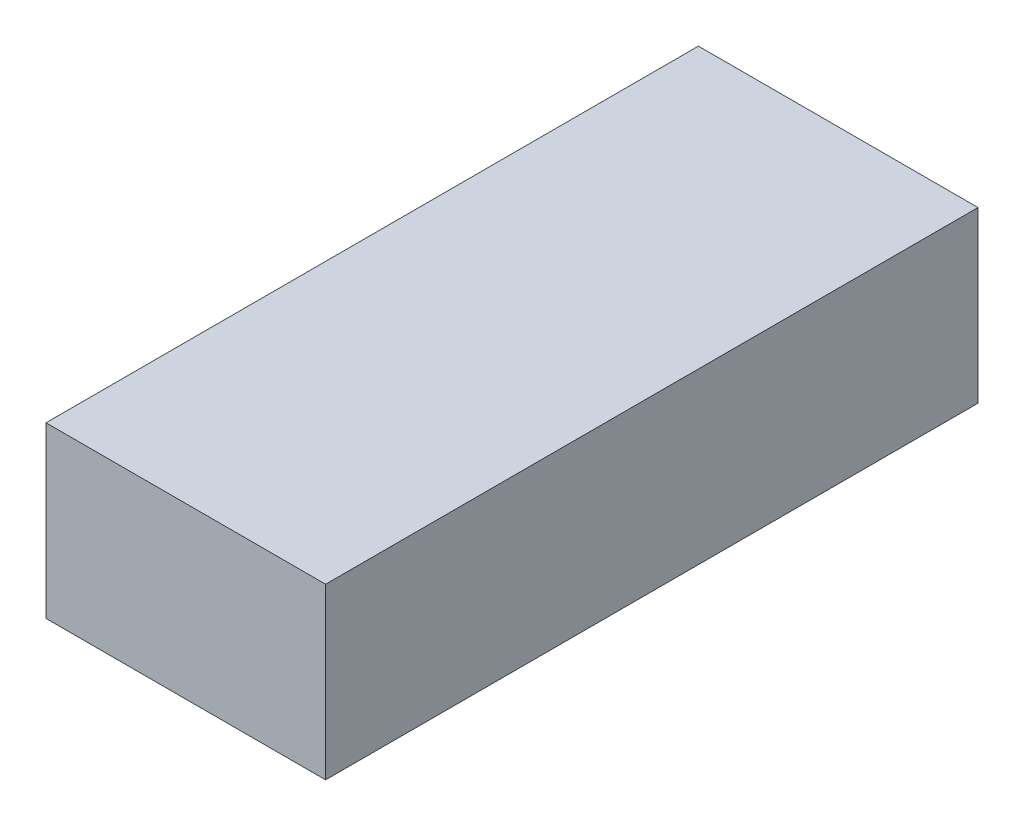
SolidWorks part; units mm, degrees
ref_plane "Front Plane" through (0, 0, 0) normal (0, 0, 1) x (1, 0, 0)
ref_plane "Top Plane" through (0, 0, 0) normal (0, 1, 0) x (1, 0, 0)
ref_plane "Right Plane" through (0, 0, 0) normal (1, 0, 0) x (0, 0, -1)
sketch "Sketch1" plane through (0, 0, 0) normal (0, 1, 0) x (1, 0, 0)
  line L0 (16.5, -38.5) -> (-16.5, -38.5)
  line L1 (16.5, -38.5) -> (16.5, 38.5)
  line L2 (-16.5, -38.5) -> (-16.5, 38.5)
  line L3 (16.5, 38.5) -> (-16.5, 38.5)
  line L4 (16.5, -38.5) -> (-16.5, 38.5) construction
  line L5 (-16.5, -38.5) -> (16.5, 38.5) construction
  point P1 (0, 0)
  dimension "D1" = 77
  dimension "D2" = 33
extrude "Boss-Extrude1" add sketch "Sketch1" along normal blind 20
